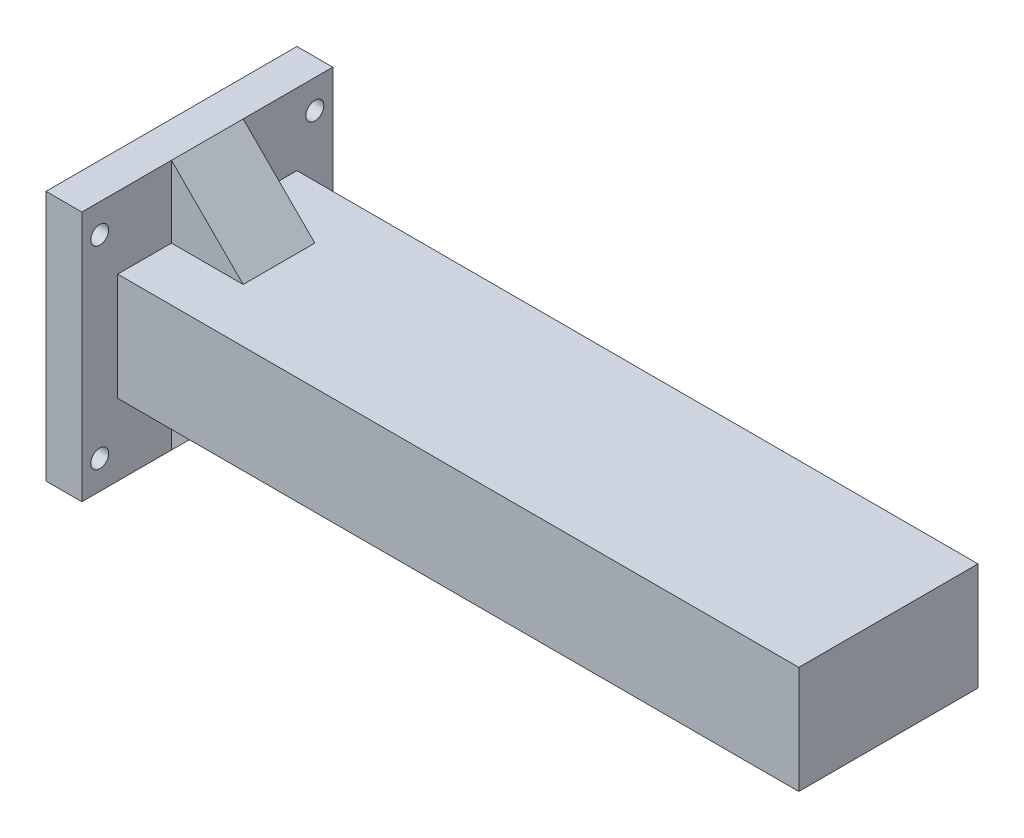
SolidWorks part; units mm, degrees
ref_plane "Front Plane" through (0, 0, 0) normal (0, 0, 1) x (1, 0, 0)
ref_plane "Top Plane" through (0, 0, 0) normal (0, 1, 0) x (1, 0, 0)
ref_plane "Right Plane" through (0, 0, 0) normal (1, 0, 0) x (0, 0, -1)
sketch "Sketch1" plane through (0, 0, 0) normal (0, 0, 1) x (1, 0, 0)
  line L5 (-50, 17.5) -> (-50, -17.5)
  line L6 (-50, -17.5) -> (-45, -17.5)
  line L8 (50, -7.5) -> (50, 7.5)
  line L10 (-45, 17.5) -> (-50, 17.5)
  line L11 (-50, 0) -> (50, 0) construction
  line L12 (-45, 17.5) -> (-45, 7.5)
  line L13 (-45, 7.5) -> (50, 7.5)
  line L14 (50, -7.5) -> (-45, -7.5)
  line L15 (-45, -7.5) -> (-45, -17.5)
  point P2 (50, 0)
  point P7 (-50, 0)
  point P11 (0, 0)
  dimension "D1" = 35
  dimension "D2" = 15
  dimension "D3" = 100
  dimension "D4" = 5
extrude "Boss-Extrude1" add sketch "Sketch1" along normal mid plane 25
sketch "Sketch2" plane through (0, 0, 0) normal (0, 0, 1) x (1, 0, 0)
  line L0 (-50, -17.5) -> (-45, -17.5) construction
  line L1 (-50, 17.5) -> (-45, 17.5)
  line L2 (-50, 17.5) -> (-50, -17.5)
  line L3 (-50, -17.5) -> (-45, -17.5)
  line L4 (-45, 17.5) -> (-45, -17.5)
  dimension "D1" = 5
extrude "Boss-Extrude2" add sketch "Sketch2" along normal mid plane 35
hole_wizard "Tap Drill for M3x0.5 Tap1" positions "Sketch3" profile "Sketch4" hole size "M3x0.5" standard "ANSI Metric" end condition through all
sketch "Sketch3" plane through (-50, 0, 0) normal (-1, 0, 0) x (0, 0, 1)
  line L0 (-15, 13.5) -> (-15, -13.5) construction
  line L1 (-15, -13.5) -> (15, -13.5) construction
  line L2 (15, -13.5) -> (15, 13.5) construction
  line L3 (15, 13.5) -> (-15, 13.5) construction
  line L5 (-17.5, 17.5) -> (-17.5, -17.5) construction
  point P0 (-15, 13.5)
  point P2 (15, 13.5)
  point P4 (15, -13.5)
  point P6 (-15, -13.5)
  point P20 (0, -13.5)
  point P22 (15, 0)
  point P23 (-15, 0)
  dimension "D1" = 27
  dimension "D2" = 2.5
sketch "Sketch4" plane through (-50, 13.5, -15) normal (0, 1, 0) x (0, 0, 1)
  line L0 (0, 0) -> (0, 100)
  line L1 (0, 100) -> (1.25, 100)
  line L2 (1.25, 100) -> (1.25, 0)
  line L5 (1.25, 0) -> (0, 0)
  line L11 (0, -6.35) -> (0, 107.95) construction
  dimension "Thru Hole Dia." = 2.5
  dimension "Thru Hole Depth" = 100
sketch "Sketch5" plane through (0, 0, 0) normal (0, 0, 1) x (1, 0, 0)
  line L0 (-45, 17.5) -> (-35, 7.5)
  line L1 (50, 7.5) -> (-45, 7.5) construction
  dimension "D1" = 45
rib "Rib1" sketch "Sketch5" sketch "Sketch5" thickness 10 extrusion direction parallel to sketch draft on no parameters "D1"=10
sketch "Sketch7" plane through (0, 0, 0) normal (0, 0, 1) x (1, 0, 0)
  line L0 (-45, -17.5) -> (-35, -7.5)
  line L1 (-45, -7.5) -> (50, -7.5) construction
  dimension "D1" = 45
rib "Rib6" sketch "Sketch7" sketch "Sketch7" thickness 10 extrusion direction parallel to sketch draft on no parameters "D1"=10
